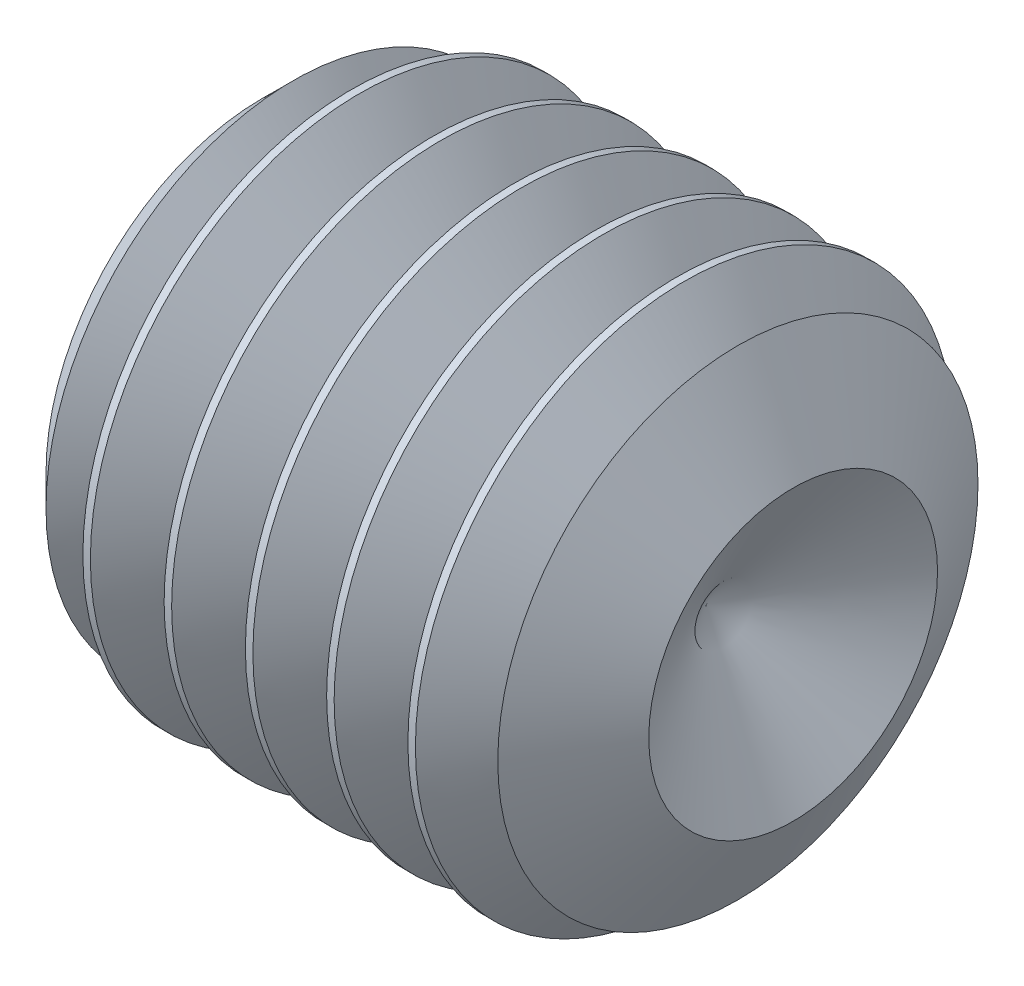
SolidWorks part; units mm, degrees
material "Chrome Stainless Steel"
ref_plane "Front Plane" through (0, 0, 0) normal (0, 0, 1) x (1, 0, 0)
ref_plane "Top Plane" through (0, 0, 0) normal (0, 1, 0) x (1, 0, 0)
ref_plane "Right Plane" through (0, 0, 0) normal (1, 0, 0) x (0, 0, -1)
ref_plane "Plane1" through (0, 0, 0) normal (0, 0, -1) x (-1, 0, 0)
sketch "Sketch1" plane through (0, 0, 0) normal (0, 0, -1) x (-1, 0, 0)
  line L0 (-4.7625, 1.2954) -> (-3.9841, 0)
  line L1 (-3.9841, 0) -> (0, 0)
  line L2 (0, 0) -> (0, 1.9406)
  line L3 (0, 1.9406) -> (-0.2779, 2.2184)
  line L4 (-0.2779, 2.2184) -> (-0.4724, 1.9406)
  line L5 (-0.4724, 1.9406) -> (-0.8032, 2.413)
  line L6 (-0.8032, 2.413) -> (-0.8706, 2.413)
  line L7 (-0.8706, 2.413) -> (-1.2014, 1.9406)
  line L8 (-1.2014, 1.9406) -> (-1.5322, 2.413)
  line L9 (-1.5322, 2.413) -> (-1.5996, 2.413)
  line L10 (-1.5996, 2.413) -> (-1.9304, 1.9406)
  line L11 (-1.9304, 1.9406) -> (-2.2612, 2.413)
  line L12 (-2.2612, 2.413) -> (-2.3285, 2.413)
  line L13 (-2.3285, 2.413) -> (-2.6593, 1.9406)
  line L14 (-2.6593, 1.9406) -> (-2.9901, 2.413)
  line L15 (-2.9901, 2.413) -> (-3.0575, 2.413)
  line L16 (-3.0575, 2.413) -> (-3.3883, 1.9406)
  line L17 (-3.3883, 1.9406) -> (-3.7191, 2.413)
  line L18 (-3.7191, 2.413) -> (-3.7864, 2.413)
  line L19 (-3.7864, 2.413) -> (-4.1173, 1.9406)
  line L20 (-4.1173, 1.9406) -> (-4.2668, 2.1541)
  line L21 (-4.2668, 2.1541) -> (-4.7625, 1.2954)
  line L22 (-4.7625, 0) -> (0, 0) construction
revolve "Revolve1" add sketch "Sketch1" angle 360 about L22
sketch "Sketch2" plane through (0, 0, 0) normal (-1, 0, 0) x (0, 0, 1)
  line L0 (1.3741, 0) -> (0.687, 1.19)
  line L1 (0.687, 1.19) -> (-0.687, 1.19)
  line L2 (-0.687, 1.19) -> (-1.3741, 0)
  line L3 (-1.3741, 0) -> (-0.687, -1.19)
  line L4 (-0.687, -1.19) -> (0.687, -1.19)
  line L5 (0.687, -1.19) -> (1.3741, 0)
extrude "Cut-Extrude1" cut sketch "Sketch2" against normal blind 2.54
